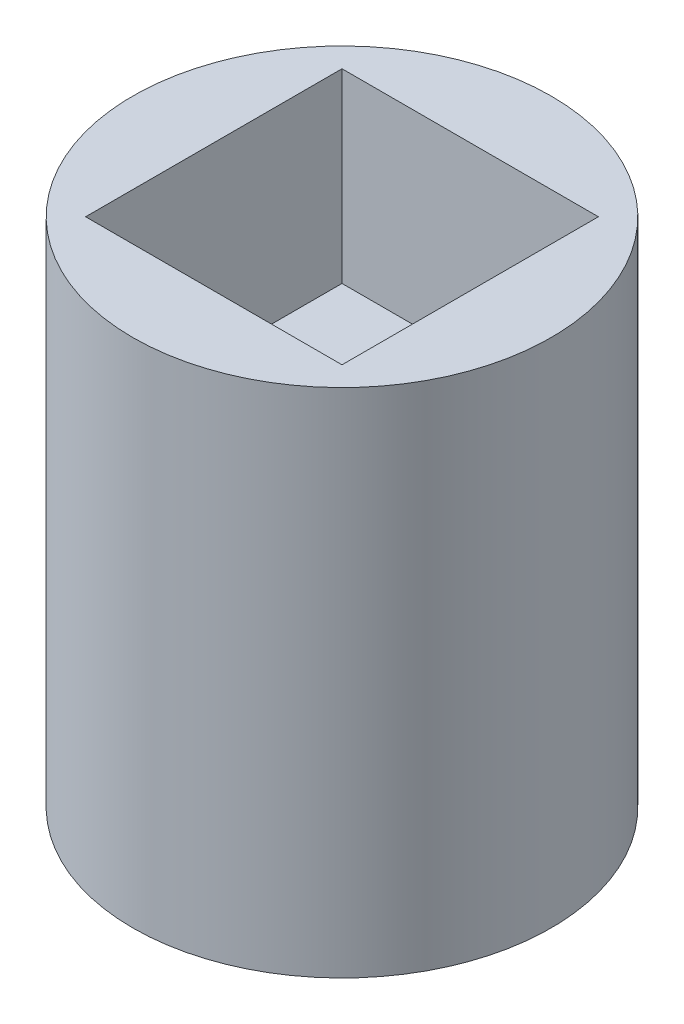
SolidWorks part; units mm, degrees
ref_plane "Plan de face" through (0, 0, 0) normal (0, 0, 1) x (1, 0, 0)
ref_plane "Plan de dessus" through (0, 0, 0) normal (0, 1, 0) x (1, 0, 0)
ref_plane "Plan de droite" through (0, 0, 0) normal (1, 0, 0) x (0, 0, -1)
sketch "Esquisse1" plane through (0, 0, 0) normal (0, 1, 0) x (1, 0, 0)
  circle A0 centre (0, 0) radius 11.25
  dimension "D1" = 22.5
extrude "Boss.-Extru.1" add sketch "Esquisse1" along normal mid plane 27.5
sketch "Esquisse3" plane through (0, 13.75, 0) normal (0, 1, 0) x (1, 0, 0)
  line L1 (-6.8943, 6.8943) -> (6.8943, 6.8943)
  line L2 (-6.8943, 6.8943) -> (-6.8943, -6.8943)
  line L3 (-6.8943, -6.8943) -> (6.8943, -6.8943)
  line L4 (6.8943, 6.8943) -> (6.8943, -6.8943)
  line L5 (-6.8943, 6.8943) -> (6.8943, -6.8943) construction
  line L6 (-6.8943, -6.8943) -> (6.8943, 6.8943) construction
  point P0 (0, 0)
  dimension "D1" = 19.5
extrude "Enlèv. mat.-Extru.3" cut sketch "Esquisse3" against normal blind 10
mirror "Symétrie1" about plane through (0, 0, 0) normal (0, 1, 0) of "Enlèv. mat.-Extru.3"
equation "\"D1@Esquisse3\"=\"D1@Esquisse1\" - 3"
